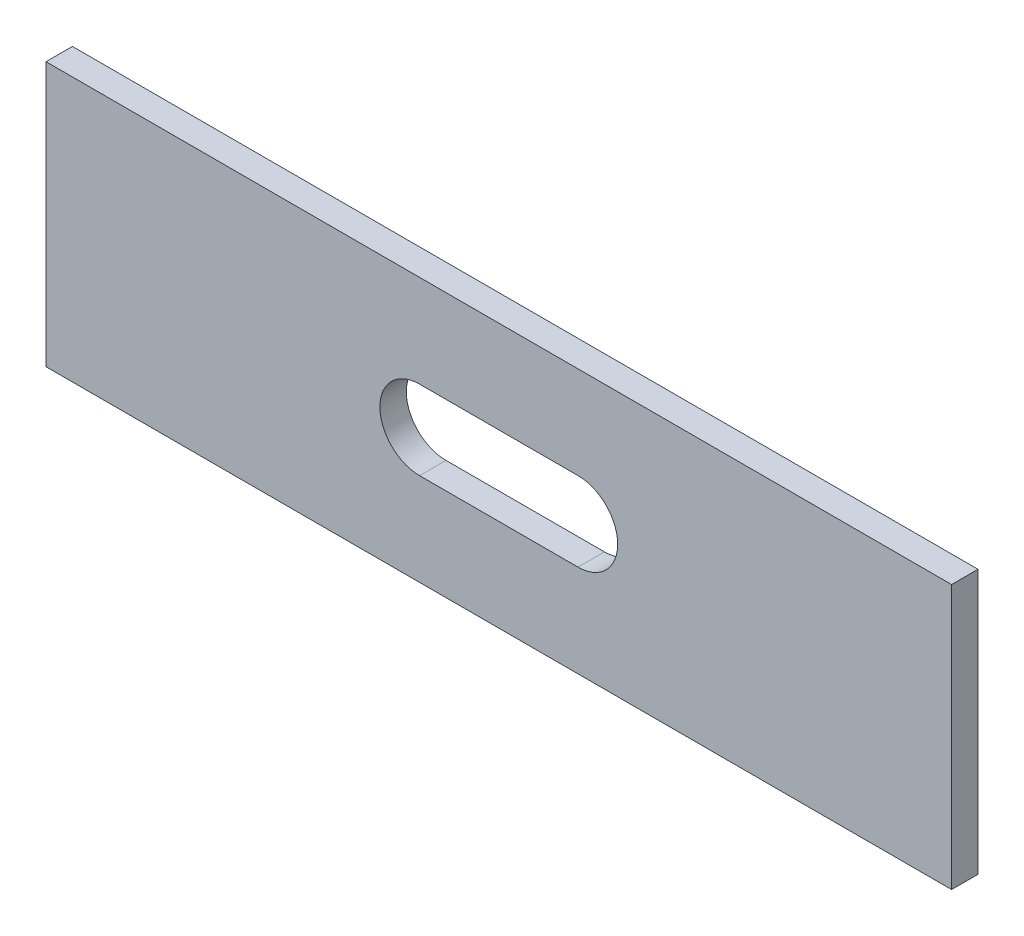
SolidWorks part; units mm, degrees
ref_plane "Front Plane" through (0, 0, 0) normal (0, 0, 1) x (1, 0, 0)
ref_plane "Top Plane" through (0, 0, 0) normal (0, 1, 0) x (1, 0, 0)
ref_plane "Right Plane" through (0, 0, 0) normal (1, 0, 0) x (0, 0, -1)
sketch "Sketch1" plane through (0, 0, 0) normal (0, 0, 1) x (1, 0, 0)
  line L1 (-108.839, -31.75) -> (108.839, -31.75)
  line L2 (-108.839, -31.75) -> (-108.839, 31.75)
  line L3 (-108.839, 31.75) -> (108.839, 31.75)
  line L4 (108.839, -31.75) -> (108.839, 31.75)
  line L5 (0, 31.75) -> (0, -31.75) construction
  line L6 (-108.839, 0) -> (108.839, 0) construction
  point P0 (0, 0)
  dimension "D1" = 217.678
  dimension "D2" = 63.5
extrude "Boss-Extrude1" add sketch "Sketch1" along normal blind 6.35
sketch "Sketch2" plane through (0, 0, 6.35) normal (0, 0, 1) x (1, 0, 0)
  line L0 (19.05, 0) -> (-19.05, 0) construction
  line L1 (19.05, -9.525) -> (-19.05, -9.525)
  line L2 (19.05, 9.525) -> (-19.05, 9.525)
  arc A0 (19.05, -9.525) -> (19.05, 9.525) centre (19.05, 0) ccw
  arc A1 (-19.05, 9.525) -> (-19.05, -9.525) centre (-19.05, 0) ccw
  point P2 (0, 0)
  dimension "D2" = 38.1
  dimension "D1" = 19.05
extrude "Cut-Extrude1" cut sketch "Sketch2" against normal through all both and the other way through all
sketch "Sketch3" plane through (0, 0, 0) normal (0, 0, -1) x (-1, 0, 0)
  line L0 (-108.839, 0) -> (108.839, 0) construction
  line L1 (-108.839, -31.75) -> (-108.839, 31.75) construction
  line L2 (108.839, 31.75) -> (108.839, -31.75) construction
  line L3 (-108.839, 31.75) -> (-108.839, -31.75) construction
  line L4 (-108.839, 31.75) -> (108.839, 31.75) construction
  line L5 (108.839, -31.75) -> (-108.839, -31.75) construction
  line L6 (0, 31.75) -> (0, -31.75) construction
  line L7 (-108.839, -6.35) -> (-96.139, -6.35) construction
  line L8 (-108.839, -6.35) -> (-108.839, 6.35)
  line L9 (-108.839, 6.35) -> (-96.139, 6.35) construction
  line L10 (-96.139, -6.35) -> (-96.139, 6.35) construction
  line L11 (-102.489, 6.35) -> (-102.489, -6.35) construction
  line L12 (-108.839, 0) -> (-96.139, 0) construction
  circle A0 centre (-102.489, 0) radius 4.699
  circle A1 centre (102.489, 0) radius 4.699
  point P12 (-102.489, 0)
  dimension "D4" = 9.398
  dimension "D2" = 12.7
  dimension "D3" = 12.7
extrude "Cut-Extrude2" cut sketch "Sketch3" against normal blind 5.842 contours A0 | A1
